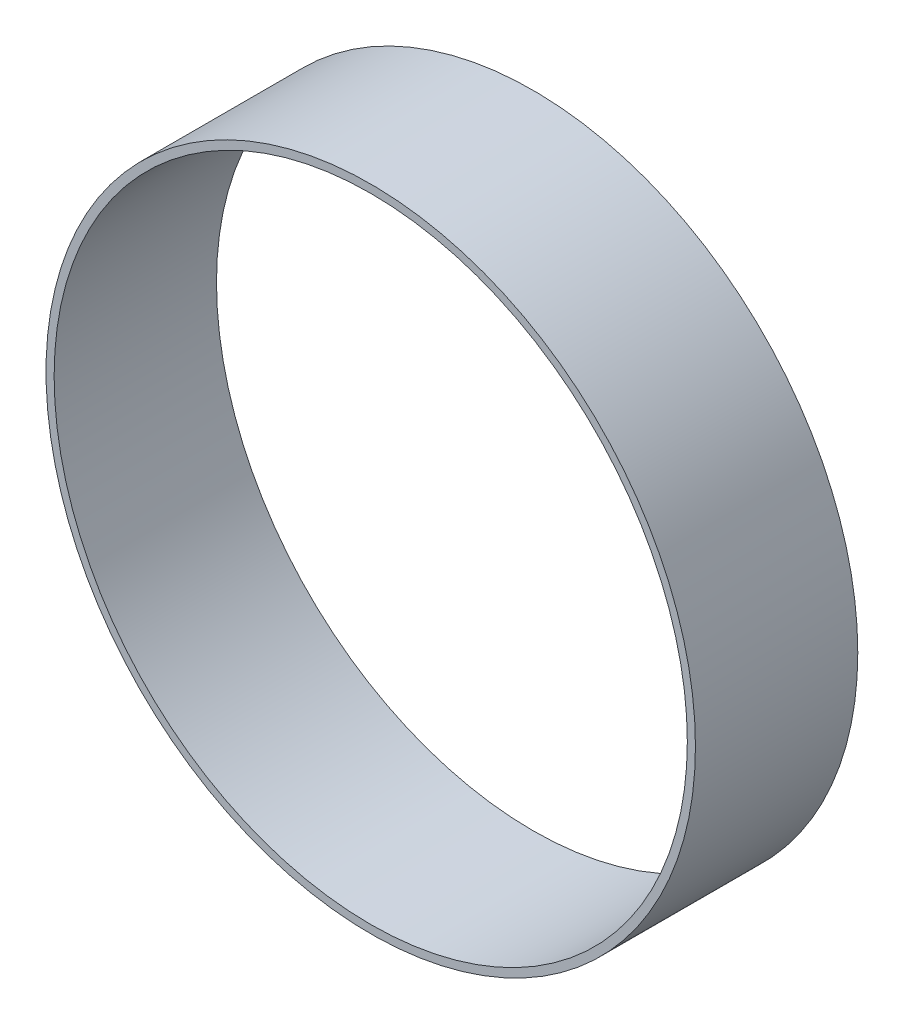
SolidWorks part; units mm, degrees
ref_plane "Front Plane" through (0, 0, 0) normal (0, 0, 1) x (1, 0, 0)
ref_plane "Top Plane" through (0, 0, 0) normal (0, 1, 0) x (1, 0, 0)
ref_plane "Right Plane" through (0, 0, 0) normal (1, 0, 0) x (0, 0, -1)
sketch "Sketch1" plane through (0, 0, 0) normal (0, 0, 1) x (1, 0, 0)
  circle A0 centre (0, 0) radius 50.8
  circle A1 centre (0, 0) radius 49.53
  dimension "D1" = 101.6
  dimension "D2" = 99.06
extrude "Boss-Extrude1" add sketch "Sketch1" along normal blind 25.4
